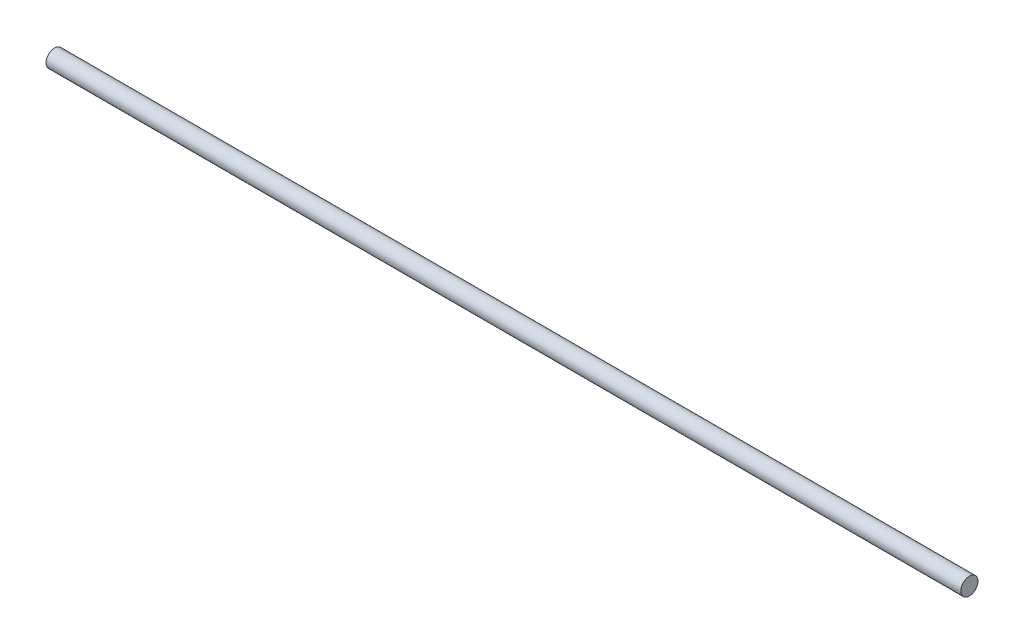
SolidWorks part; units mm, degrees
ref_plane "Front Plane" through (0, 0, 0) normal (0, 0, 1) x (1, 0, 0)
ref_plane "Top Plane" through (0, 0, 0) normal (0, 1, 0) x (1, 0, 0)
ref_plane "Right Plane" through (0, 0, 0) normal (1, 0, 0) x (0, 0, -1)
sketch "Sketch1" plane through (0, 0, 0) normal (1, 0, 0) x (0, 0, -1)
  circle A0 centre (0, 0) radius 4
  dimension "D1" = 8
extrude "Boss-Extrude1" add sketch "Sketch1" along normal blind 425
